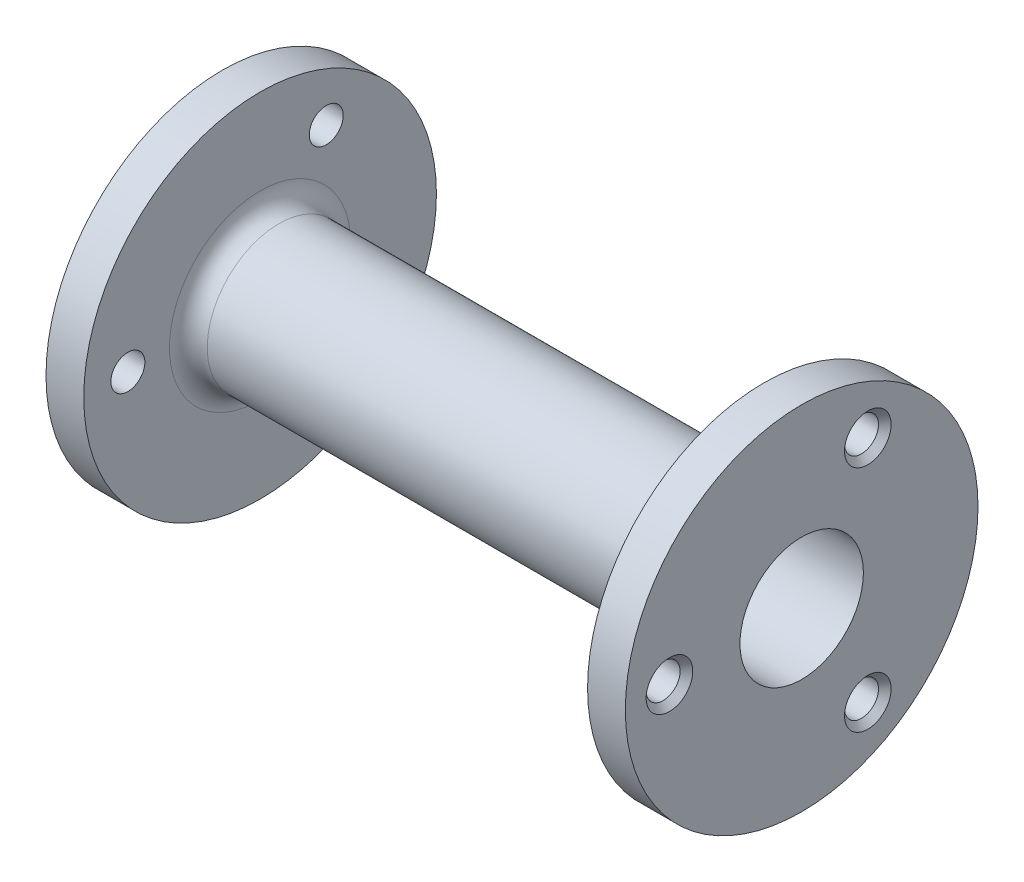
SolidWorks part; units mm, degrees
ref_plane "Front Plane" through (0, 0, 0) normal (0, 0, 1) x (1, 0, 0)
ref_plane "Top Plane" through (0, 0, 0) normal (0, 1, 0) x (1, 0, 0)
ref_plane "Right Plane" through (0, 0, 0) normal (1, 0, 0) x (0, 0, -1)
sketch "Sketch1" plane through (0, 0, 0) normal (0, 0, 1) x (1, 0, 0)
  line L0 (0, 4.9) -> (0, 14)
  line L1 (0, 0) -> (-13.4865, 0) construction
  line L2 (0, 14) -> (3, 14)
  line L3 (3, 14) -> (3, 7.2)
  line L4 (3, 4.9) -> (43, 4.9)
  line L5 (4.5, 5.7) -> (41.5, 5.7)
  line L6 (3, 4.9) -> (0, 4.9)
  line L7 (43, 7.2) -> (43, 14)
  line L8 (43, 14) -> (46, 14)
  line L9 (46, 14) -> (46, 4.9)
  line L10 (46, 4.9) -> (43, 4.9)
  arc A0 (41.5, 5.7) -> (43, 7.2) centre (41.5, 7.2) ccw
  arc A1 (4.5, 5.7) -> (3, 7.2) centre (4.5, 7.2) cw
  point P17 (3, 5.7)
  dimension "D1" = 9.8
  dimension "D2" = 3
  dimension "D6" = 1.5
  dimension "D3" = 28
  dimension "D4" = 0.8
  dimension "D5" = 40
revolve "Revolve1" add sketch "Sketch1" angle 360 about L1
sketch "Sketch3" plane through (46, 0, 0) normal (1, 0, 0) x (0, 0, -1)
  line L0 (-10.5, 0) -> (0, 0) construction
  circle A0 centre (-10.5, 0) radius 1.35
  circle A1 centre (0, 0) radius 14 construction
  circle A3 centre (5.25, 9.0933) radius 1.35
  circle A4 centre (5.25, -9.0933) radius 1.35
  point P4 (-14, 0)
  point P13 (0, 0)
  dimension "D1" = 10.5
  dimension "D2" = 2.7
  dimension "D3" = 3
extrude "Cut-Extrude1" cut sketch "Sketch3" against normal through all
chamfer "Chamfer1" distance 0.5 angle 45 6 edges at (46, 0, 9.15) (46, -9.0933, -6.6) (46, 9.0933, -6.6) (0, -9.0933, -6.6) (0, 9.0933, -6.6) (0, 0, 9.15)
